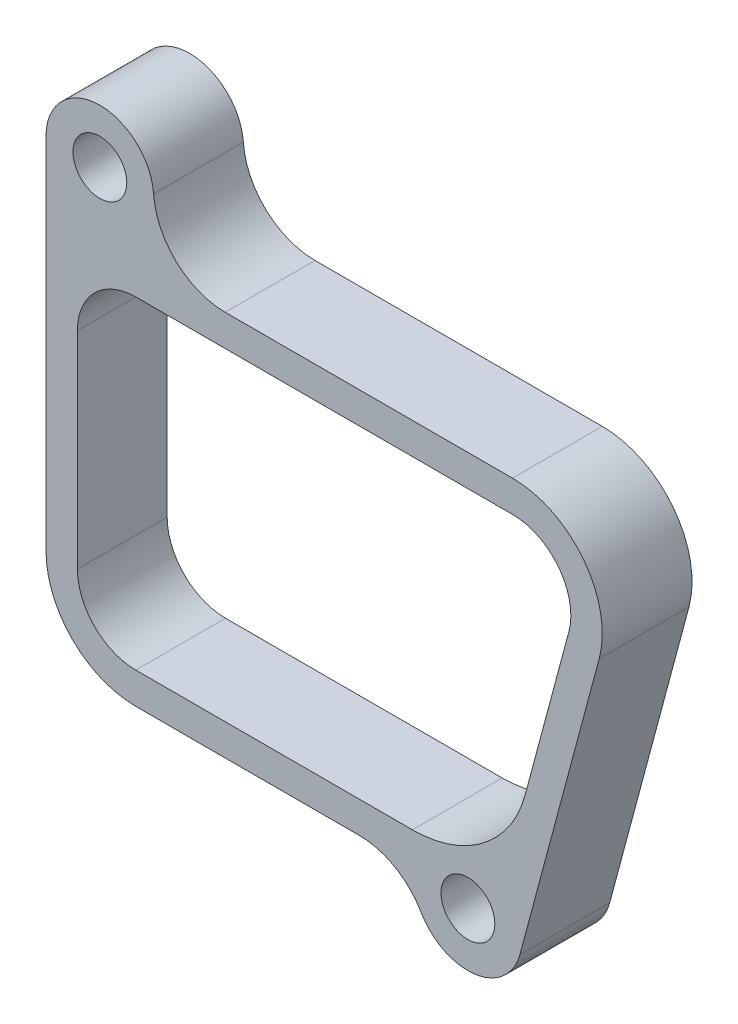
SolidWorks part; units mm, degrees
ref_plane "Front Plane" through (0, 0, 0) normal (0, 0, 1) x (1, 0, 0)
ref_plane "Top Plane" through (0, 0, 0) normal (0, 1, 0) x (1, 0, 0)
ref_plane "Right Plane" through (0, 0, 0) normal (1, 0, 0) x (0, 0, -1)
sketch "Sketch1" plane through (0, 0, 0) normal (0, 0, 1) x (1, 0, 0)
  line L0 (-12, 0) -> (-12, -80)
  line L1 (-5, -34) -> (-5, -80)
  line L2 (8, -93) -> (69.6374, -93)
  line L3 (8, -100) -> (57.7513, -100)
  line L4 (8, -21) -> (91.9383, -21)
  line L5 (27.9285, -14) -> (91.9383, -14)
  line L6 (93.5911, -105.1058) -> (111.2569, -39.1764)
  line L7 (94.7515, -73.7293) -> (104.4954, -37.3646)
  line L8 (0, -102) -> (82, -102) construction
  circle A0 centre (0, 0) radius 12
  circle A1 centre (0, 0) radius 6
  arc A2 (11.9693, 0.8571) -> (27.9285, -14) centre (27.9285, 2) ccw
  arc A3 (-5, -34) -> (8, -21) centre (8, -34) cw
  arc A4 (8, -93) -> (-5, -80) centre (8, -80) cw
  arc A5 (8, -100) -> (-12, -80) centre (8, -80) cw
  circle A6 centre (82, -102) radius 6
  arc A7 (71.6077, -108) -> (93.5911, -105.1058) centre (82, -102) ccw
  arc A8 (71.6077, -108) -> (57.7513, -100) centre (57.7513, -116) ccw
  arc A9 (69.6374, -93) -> (94.7515, -73.7293) centre (69.6374, -67) ccw
  arc A10 (104.4954, -37.3646) -> (91.9383, -21) centre (91.9383, -34) ccw
  arc A11 (111.2569, -39.1764) -> (91.9383, -14) centre (91.9383, -34) ccw
  dimension "D1" = 24
  dimension "D2" = 12
  dimension "D3" = 32
  dimension "D7" = 13
  dimension "D9" = 13
  dimension "D10" = 20
  dimension "D11" = 12
  dimension "D12" = 24
  dimension "D14" = 32
  dimension "D15" = 52
  dimension "D19" = 26
  dimension "D20" = 40
  dimension "D4" = 7
  dimension "D5" = 7
  dimension "D6" = 7
  dimension "D8" = 100
  dimension "D13" = 2
  dimension "D16" = 105
  dimension "D17" = 94
  dimension "D18" = 7
  dimension "D21" = 86
extrude "Boss-Extrude2" add sketch "Sketch1" along normal mid plane 20
